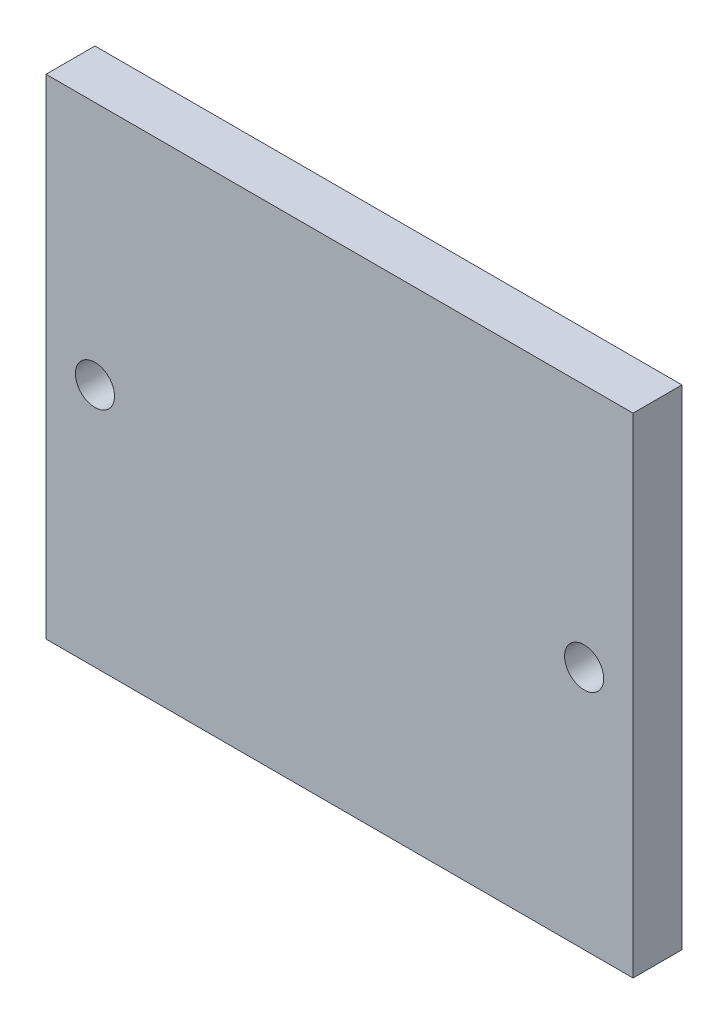
SolidWorks part; units mm, degrees
ref_plane "Plan de face" through (0, 0, 0) normal (0, 0, 1) x (1, 0, 0)
ref_plane "Plan de dessus" through (0, 0, 0) normal (0, 1, 0) x (1, 0, 0)
ref_plane "Plan de droite" through (0, 0, 0) normal (1, 0, 0) x (0, 0, -1)
sketch "Esquisse1" plane through (0, 0, 0) normal (0, 0, 1) x (1, 0, 0)
  line L0 (0, 38.5176) -> (0, -48.9415) construction
  line L1 (-30, 25) -> (30, 25)
  line L2 (-30, 25) -> (-30, -25)
  line L3 (-30, -25) -> (30, -25)
  line L4 (30, 25) -> (30, -25)
  line L5 (-30, 25) -> (30, -25) construction
  line L6 (-30, -25) -> (30, 25) construction
  circle A0 centre (25, 0) radius 2
  circle A1 centre (-25, 0) radius 2
  point P0 (0, 0)
  dimension "D3" = 5
  dimension "D4" = 4
  dimension "D1" = 60
  dimension "D2" = 50
  dimension "D5" = 25
extrude "Boss.-Extru.1" add sketch "Esquisse1" along normal blind 5
